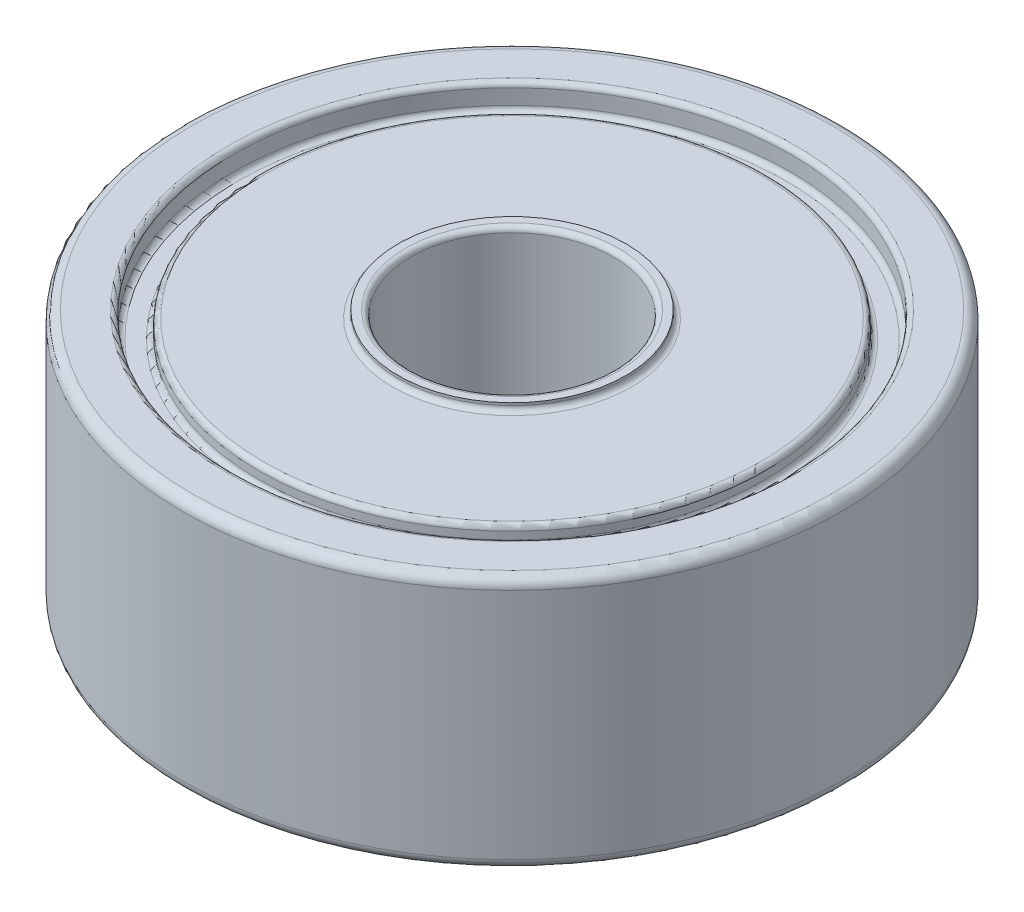
SolidWorks part; units mm, degrees
material "Plain Carbon Steel"
ref_plane "Front Plane" through (0, 0, 0) normal (0, 0, 1) x (1, 0, 0)
ref_plane "Top Plane" through (0, 0, 0) normal (0, 1, 0) x (1, 0, 0)
ref_plane "Right Plane" through (0, 0, 0) normal (1, 0, 0) x (0, 0, -1)
sketch "Sketch1" plane through (0, 0, 0) normal (0, 1, 0) x (1, 0, 0)
  circle A0 centre (0, 0) radius 6.5
  dimension "D1" = 13
extrude "Boss-Extrude1" add sketch "Sketch1" along normal mid plane 5
sketch "Sketch2" plane through (0, 2.5, 0) normal (0, 1, 0) x (1, 0, 0)
  circle A0 centre (0, 0) radius 2
  dimension "D1" = 4
extrude "Cut-Extrude1" cut sketch "Sketch2" against normal blind 5
fillet "Fillet1" radius 0.2 2 edges at (0, -2.5, 6.5) (0, 2.5, 6.5)
sketch "Sketch4" plane through (0, 0, 0) normal (0, 0, 1) x (1, 0, 0)
  line L0 (-5.5, 2.5) -> (-5.5, 2)
  line L1 (6.3, 2.5) -> (-6.3, 2.5) construction
  line L2 (-5.5, 2) -> (-5, 2)
  line L3 (-6.5, 2.3) -> (-6.5, -2.3) construction
  line L5 (-5, 2) -> (-5, 2.35)
  line L6 (-5, 2.35) -> (-2.25, 2.35)
  line L7 (-2.25, 2.35) -> (-2.25, 2.5)
  line L9 (0, 0) -> (0, 2.5) construction
  line L10 (2, 2.5) -> (-2, 2.5) construction
  line L11 (-5.5, 2.5) -> (-2.25, 2.5)
  dimension "D1" = 1
  dimension "D2" = 0.5
  dimension "D3" = 1.5
  dimension "D4" = 2.75
  dimension "D5" = 0.15
revolve "Cut-Revolve1" cut sketch "Sketch4" angle 360 about L9
mirror "Mirror1" about plane through (0, 0, 0) normal (0, 1, 0) of "Cut-Revolve1"
fillet "Fillet3" radius 0.1 10 edges at (0, -2, -5.5) (0, 2, -5) (0, 2.5, -5.5) (0, 2, -5.5) (0, 2.35, -5) (0, 2.35, -2.25) (0, 2.5, 2) (0, -2.5, 2) (0, -2.35, -5) (0, -2, -5)
